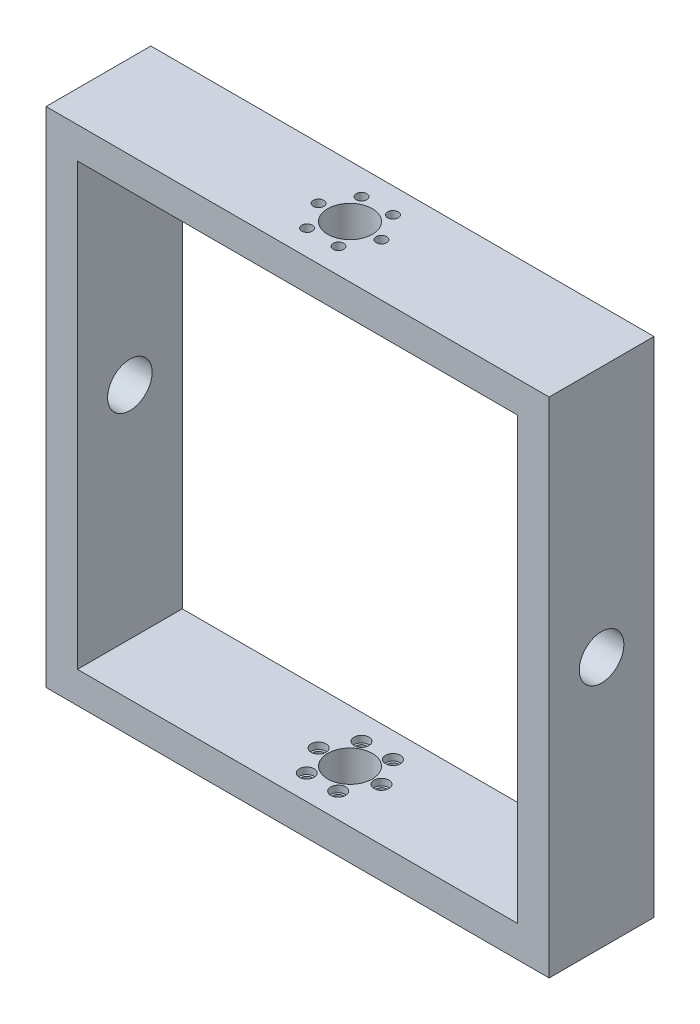
SolidWorks part; units mm, degrees
ref_plane "Front Plane" through (0, 0, 0) normal (0, 0, 1) x (1, 0, 0)
ref_plane "Top Plane" through (0, 0, 0) normal (0, 1, 0) x (1, 0, 0)
ref_plane "Right Plane" through (0, 0, 0) normal (1, 0, 0) x (0, 0, -1)
sketch "Sketch1" plane through (0, 0, 0) normal (0, 0, 1) x (1, 0, 0)
  line L0 (76.2, 0) -> (66.675, 0) construction
  line L1 (-76.2, 0) -> (76.2, 0) construction
  line L2 (0, 76.2) -> (0, -76.2)
  point P7 (0, 0)
sketch "Sketch2" plane through (0, 0, 0) normal (1, 0, 0) x (0, 0, -1)
  line L0 (76.2, 0) -> (-76.2, 0)
  point P4 (0, 0)
  dimension "Length" = 152.4
sketch "Sketch3" plane through (0, 0, 0) normal (0, 0, 1) x (1, 0, 0)
  line L0 (-76.2, 0) -> (76.2, 0) construction
  line L5 (76.2, -76.2) -> (-76.2, -76.2)
  line L6 (76.2, -76.2) -> (76.2, 76.2)
  line L11 (76.2, 76.2) -> (-76.2, 76.2)
  line L12 (-76.2, -76.2) -> (-76.2, 76.2)
  line L14 (76.2, -76.2) -> (-76.2, 76.2) construction
  line L15 (76.2, 76.2) -> (-76.2, -76.2) construction
  line L16 (66.675, -66.675) -> (-66.675, -66.675)
  line L17 (66.675, -66.675) -> (66.675, 66.675)
  line L18 (66.675, 66.675) -> (-66.675, 66.675)
  line L19 (-66.675, -66.675) -> (-66.675, 66.675)
  line L20 (66.675, -66.675) -> (-66.675, 66.675) construction
  line L21 (66.675, 66.675) -> (-66.675, -66.675) construction
  point P0 (0, 0)
  point P5 (0, 0)
  point P13 (66.675, -76.2)
  dimension "D1" = 9.525
  dimension "D3" = 152.4
  dimension "D4" = 152.4
  dimension "D2" = 9.525
extrude "Boss-Extrude1" add sketch "Sketch3" along normal up to vertex (76.2 mm away) and the other way up to vertex (76.2 mm away) up to point (0, 0, 76.2) other way up to point (0, 0, -76.2)
sketch "Sketch5" plane through (0, 0, 0) normal (1, 0, 0) x (0, 0, -1)
  line L0 (-76.2, 0) -> (76.2, 0) construction
  line L3 (-76.2, -76.2) -> (-76.2, 76.2) construction
  line L4 (76.2, -76.2) -> (76.2, 76.2) construction
  point P6 (95.25, 0)
  point P7 (152.4, 0)
  point P8 (-152.4, 0)
  point P10 (-95.25, 0)
  dimension "D1" = 171.45
  dimension "D2" = 228.6
  dimension "D3" = 171.45
  dimension "D4" = 228.6
sketch "Sketch6" plane through (0, 76.2, 0) normal (0, 1, 0) x (1, 0, 0)
  line L0 (76.2, -76.2) -> (76.2, 76.2) construction
  line L1 (-76.2, 76.2) -> (76.2, 76.2)
  line L2 (-76.2, 76.2) -> (-76.2, -44.45)
  line L3 (-76.2, -44.45) -> (76.2, -44.45)
  line L4 (76.2, 76.2) -> (76.2, -44.45)
  line L5 (76.2, -76.2) -> (-76.2, -76.2) construction
  dimension "D1" = 31.75
extrude "Cut-Extrude1" cut sketch "Sketch6" against normal through all
sketch "Sketch7" plane through (0, 76.2, 0) normal (0, 1, 0) x (1, 0, 0)
  line L0 (-76.2, -44.45) -> (76.2, -44.45) construction
  line L1 (76.2, -76.2) -> (76.2, -44.45) construction
  point P0 (0, -60.325)
  point P3 (0, -44.45)
  point P6 (76.2, -60.325)
hole_wizard "M12 Clearance Hole1" positions "Sketch8" profile "Sketch10" hole size "M12" standard "ANSI Metric" end condition through all
sketch "Sketch8" plane through (0, 76.2, 0) normal (0, 1, 0) x (1, 0, 0)
  point P0 (0, -60.325)
sketch "Sketch10" plane through (0, 76.2, 60.325) normal (1, 0, 0) x (0, 0, 1)
  line L0 (0, 0) -> (0, 152.4)
  line L1 (0, 152.4) -> (6.75, 152.4)
  line L2 (6.75, 152.4) -> (6.75, 0)
  line L5 (6.75, 0) -> (0, 0)
  line L11 (0, -6.35) -> (0, 107.95) construction
  dimension "Thru Hole Dia." = 13.5
  dimension "Thru Hole Depth" = 152.4
sketch "Sketch11" plane through (76.2, 0, 0) normal (1, 0, 0) x (0, 0, -1)
  line L0 (-76.2, 76.2) -> (-44.45, 76.2) construction
  line L1 (-44.45, -76.2) -> (-44.45, 76.2) construction
  point P0 (-60.325, 0)
  point P3 (-60.325, 76.2)
  point P6 (-44.45, 0)
hole_wizard "M8 Clearance Hole2" positions "Sketch12" profile "Sketch13" hole size "M8" standard "ANSI Metric"
sketch "Sketch12" plane through (76.2, 0, 0) normal (1, 0, 0) x (0, 0, -1)
  point P0 (-60.325, 0)
sketch "Sketch13" plane through (76.2, 0, 60.325) normal (0, 1, 0) x (0, 0, -1)
  line L0 (0, 0) -> (0, 152.4)
  line L1 (0, 152.4) -> (4.5, 152.4)
  line L2 (4.5, 152.4) -> (4.5, 0)
  line L5 (4.5, 0) -> (0, 0)
  line L11 (0, -6.35) -> (0, 107.95) construction
  dimension "Thru Hole Dia." = 9
  dimension "Thru Hole Depth" = 152.4
hole_wizard "M12 Clearance Hole2" positions "Sketch14" profile "Sketch15" hole size "M12" standard "ANSI Metric" end condition through all
sketch "Sketch14" plane through (76.2, 0, 0) normal (1, 0, 0) x (0, 0, -1)
  point P0 (-60.325, 0)
sketch "Sketch15" plane through (76.2, 0, 60.325) normal (0, 1, 0) x (0, 0, -1)
  line L0 (0, 0) -> (0, 152.4)
  line L1 (0, 152.4) -> (6.75, 152.4)
  line L2 (6.75, 152.4) -> (6.75, 0)
  line L5 (6.75, 0) -> (0, 0)
  line L11 (0, -6.35) -> (0, 107.95) construction
  dimension "Thru Hole Dia." = 13.5
  dimension "Thru Hole Depth" = 152.4
hole_wizard "M16 Clearance Hole2" positions "Sketch16" profile "Sketch17" hole size "M16" standard "ANSI Metric"
sketch "Sketch16" plane through (0, -76.2, 0) normal (0, -1, 0) x (-1, 0, 0)
  point P0 (0, -60.325)
sketch "Sketch17" plane through (0, -76.2, 60.325) normal (1, 0, 0) x (0, 0, -1)
  line L0 (0, 0) -> (0, 14.7815)
  line L1 (0, 14.7815) -> (8.75, 9.524)
  line L2 (8.75, 9.524) -> (8.75, 0)
  line L5 (8.75, 0) -> (0, 0)
  line L10 (0, 14.7815) -> (-8.75, 9.524) construction
  line L11 (0, -6.35) -> (0, 107.95) construction
  dimension "Hole Dia." = 17.5
  dimension "Hole Depth" = 9.524
  dimension "Drill Angle" = 118
sketch "Sketch18" plane through (0, 76.2, 0) normal (0, 1, 0) x (1, 0, 0)
  point P0 (4.7625, -68.5739)
  point P1 (-4.7625, -68.5739)
  point P3 (-9.525, -60.325)
  point P5 (-4.7625, -52.0761)
  point P7 (4.7625, -52.0761)
  point P9 (9.525, -60.325)
hole_wizard "CBORE for M3 SHCS2" positions "Sketch19" profile "Sketch21" counterbore size "M3" standard "ANSI Metric"
sketch "Sketch19" plane through (0, 66.675, 0) normal (0, -1, 0) x (-1, 0, 0)
  point P0 (-4.7625, -68.5739)
  point P3 (-4.7625, -52.0761)
  point P6 (-9.525, -60.325)
  point P9 (9.525, -60.325)
  point P12 (4.7625, -52.0761)
  point P15 (4.7625, -68.5739)
sketch "Sketch21" plane through (4.7625, 66.675, 68.5739) normal (1, 0, 0) x (0, 0, -1)
  line L0 (0, 0) -> (0, 9.525)
  line L1 (0, 9.525) -> (1.6, 9.525)
  line L3 (1.6, 9.525) -> (1.6, 2)
  line L4 (1.6, 2) -> (2.25, 2)
  line L5 (2.25, 2) -> (2.25, 0)
  line L7 (2.25, 0) -> (0, 0)
  line L11 (0, -6.35) -> (0, 107.95) construction
  dimension "Thru Hole Dia." = 3.2
  dimension "Thru Hole Depth" = 9.525
  dimension "C'Bore Dia." = 4.5
  dimension "C'Bore Depth" = 2
sketch "Sketch22" plane through (0, -66.675, 0) normal (0, 1, 0) x (1, 0, 0)
  point P0 (4.7625, -52.0761)
  point P1 (9.525, -60.325)
  point P3 (-4.7625, -52.0761)
  point P5 (-9.525, -60.325)
  point P7 (-4.7625, -68.6643)
  point P9 (4.7625, -68.6643)
hole_wizard "CBORE for M3 SHCS3" positions "Sketch25" profile "Sketch26" counterbore size "M3" standard "ANSI Metric"
sketch "Sketch25" plane through (0, -66.675, 0) normal (0, 1, 0) x (1, 0, 0)
  point P0 (4.7625, -52.0761)
  point P3 (9.525, -60.325)
  point P6 (4.7625, -68.6643)
  point P9 (-4.7625, -68.6643)
  point P12 (-9.525, -60.325)
  point P15 (-4.7625, -52.0761)
sketch "Sketch26" plane through (4.7625, -66.675, 52.0761) normal (1, 0, 0) x (0, 0, 1)
  line L0 (0, 0) -> (0, 9.525)
  line L1 (0, 9.525) -> (1.6, 9.525)
  line L3 (1.6, 9.525) -> (1.6, 2)
  line L4 (1.6, 2) -> (2.25, 2)
  line L5 (2.25, 2) -> (2.25, 0)
  line L7 (2.25, 0) -> (0, 0)
  line L11 (0, -6.35) -> (0, 107.95) construction
  dimension "Thru Hole Dia." = 3.2
  dimension "Thru Hole Depth" = 9.525
  dimension "C'Bore Dia." = 4.5
  dimension "C'Bore Depth" = 2
equation "\"D1@Sketch3\"=\"Wall thickness@Sketch1\""
equation "\"D1@Sketch5\"=\"Width@Sketch1\"*1.125"
equation "\"D2@Sketch5\"=\"Width@Sketch1\"*1.5"
equation "\"D3@Sketch5\"=\"D1@Sketch5\""
equation "\"D4@Sketch5\"=\"D2@Sketch5\""
equation "\"D2@Sketch3\"=\"Wall Thickness@Sketch1\""
